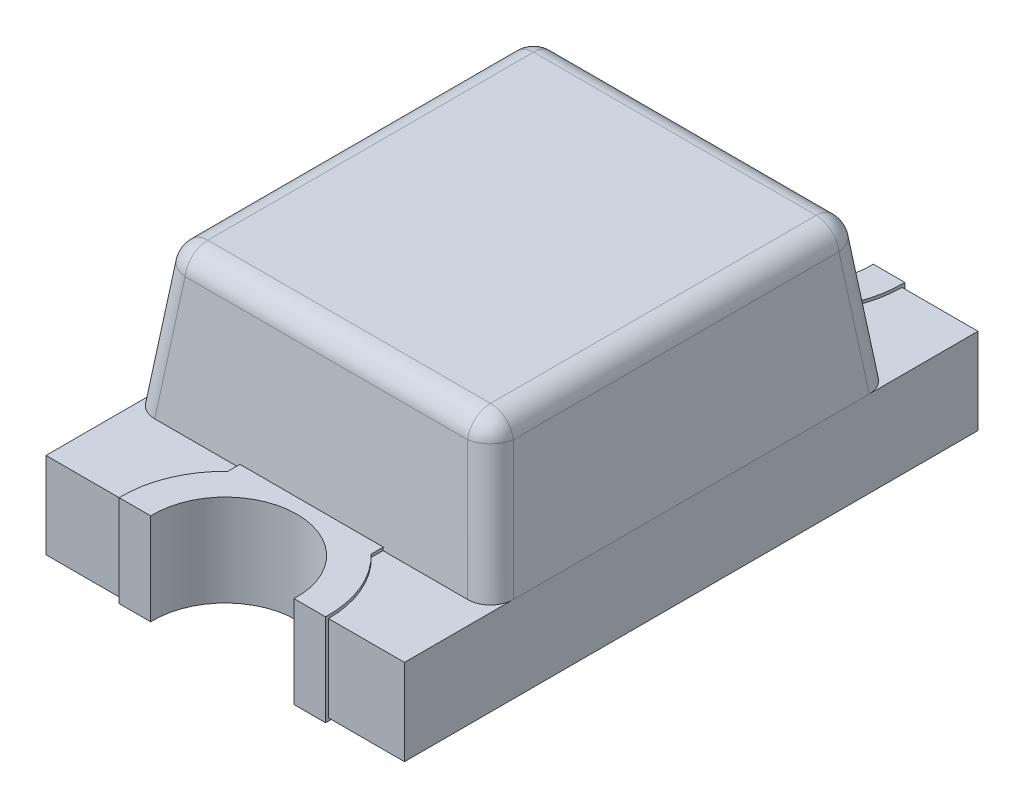
SolidWorks part; units mm, degrees
ref_plane "Front Plane" through (0, 0, 0) normal (0, 0, 1) x (1, 0, 0)
ref_plane "Top Plane" through (0, 0, 0) normal (0, 1, 0) x (1, 0, 0)
ref_plane "Right Plane" through (0, 0, 0) normal (1, 0, 0) x (0, 0, -1)
sketch "Sketch1" plane through (0, 0, 0) normal (0, 1, 0) x (1, 0, 0)
  line L0 (-0.625, 1) -> (0.625, -1) construction
  line L1 (-0.625, -1) -> (-0.25, -1)
  line L2 (-0.625, -1) -> (-0.625, 1)
  line L3 (-0.625, 1) -> (-0.25, 1)
  line L4 (0.625, -1) -> (0.625, 1)
  line L5 (-0.625, -1) -> (0.625, 1) construction
  line L6 (0.25, 1) -> (0.625, 1)
  line L7 (0.25, -1) -> (0.625, -1)
  arc A0 (-0.25, 1) -> (0.25, 1) centre (0, 1) ccw
  arc A1 (0.25, -1) -> (-0.25, -1) centre (0, -1) ccw
  dimension "D2" = 0.5
  dimension "D1" = 2
  dimension "D3" = 1.25
extrude "Base" add sketch "Sketch1" along normal mid plane 0.3
sketch "Sketch8" plane through (0, 0, 0) normal (0, 1, 0) x (1, 0, 0)
  line L0 (-0.25, -0.741) -> (-0.25, -0.6)
  line L1 (-0.25, -0.6) -> (0.25, -0.6)
  line L2 (0.25, -0.6) -> (0.25, -0.741)
  line L3 (-0.3599, 1.01) -> (-0.2498, 1.01)
  line L6 (-0.625, 1) -> (-0.625, -1)
  line L7 (-0.625, -1) -> (-0.25, -1)
  line L8 (0.25, -1) -> (0.625, -1)
  line L9 (0.625, -1) -> (0.625, 1)
  line L10 (0.625, 1) -> (0.25, 1)
  line L11 (-0.25, 1) -> (-0.625, 1)
  line L20 (0.2498, 1.01) -> (0.3599, 1.01)
  line L21 (0.625, 1) -> (0.25, 1) construction
  line L22 (-0.3599, -1.01) -> (-0.2498, -1.01)
  line L23 (0.2498, -1.01) -> (0.3599, -1.01)
  line L24 (0.25, -1) -> (0.625, -1) construction
  arc A0 (-0.3599, 1.01) -> (0.3599, 1.01) centre (0, 1) ccw
  arc A1 (0.3599, -1.01) -> (0.25, -0.741) centre (0, -1) ccw
  arc A2 (0.25, -1) -> (-0.25, -1) centre (0, -1) ccw
  arc A3 (-0.25, 1) -> (0.25, 1) centre (0, 1) ccw
  arc A4 (0.2498, -1.01) -> (-0.2498, -1.01) centre (0, -1) ccw
  arc A5 (-0.2498, 1.01) -> (0.2498, 1.01) centre (0, 1) ccw
  arc A6 (-0.25, -0.741) -> (-0.3599, -1.01) centre (0, -1) ccw
  arc A7 (-0.25, 1) -> (0.25, 1) centre (0, 1) ccw construction
  arc A8 (-0.36, 1) -> (0.36, 1) centre (0, 1) ccw construction
  dimension "D2" = 0.36
  dimension "D3" = 0.5
  dimension "D4" = 0.6
  dimension "D5" = 0.01
  dimension "D6" = 0.01
  dimension "D1" = 0
extrude "Lead top" add sketch "Sketch8" along normal mid plane 0.32
sketch "Sketch10" plane through (0, -0.16, 0) normal (0, -1, 0) x (1, 0, 0)
  line L0 (0, 0.6) -> (0, 0) construction
  line L5 (-0.25, 0.741) -> (-0.25, 0.6)
  line L6 (-0.25, 0.6) -> (0.25, 0.6)
  line L7 (0.3599, -1.01) -> (0.2498, -1.01) construction
  line L8 (-0.2498, -1.01) -> (-0.3599, -1.01) construction
  line L16 (-0.3599, 1.01) -> (-0.3599, 0.6)
  line L17 (-0.3599, 0.6) -> (0.3599, 0.6)
  line L18 (0.3599, 1.01) -> (0.3599, 0.6)
  line L19 (-0.3599, -0.6) -> (0.3599, -0.6)
  line L23 (0, 0) -> (0, -0.6) construction
  line L26 (0.36, 1) -> (0.625, 1) construction
  line L31 (0.3599, -1.01) -> (0.2498, -1.01)
  line L32 (-0.2498, -1.01) -> (-0.3599, -1.01)
  line L33 (-0.2498, 1.01) -> (-0.3599, 1.01)
  line L34 (-0.2498, 1.01) -> (-0.3599, 1.01)
  line L35 (0.25, 0.6) -> (0.25, 0.741)
  line L36 (0.3599, 1.01) -> (0.2498, 1.01)
  line L37 (0.3599, 1.01) -> (0.2498, 1.01)
  line L38 (0.3599, -1.01) -> (0.3599, -0.6)
  line L40 (-0.3599, -1.01) -> (-0.3599, -0.6)
  arc A3 (-0.2498, 1.01) -> (0.2498, 1.01) centre (0, 1) ccw
  arc A4 (-0.3599, 1.01) -> (-0.25, 0.741) centre (0, 1) ccw
  arc A5 (-0.2498, 1.01) -> (0.2498, 1.01) centre (0, 1) ccw
  arc A12 (0.2498, -1.01) -> (-0.2498, -1.01) centre (0, -1) ccw construction
  arc A16 (0.25, 0.741) -> (0.3599, 1.01) centre (0, 1) ccw
  arc A17 (0.2498, -1.01) -> (-0.2498, -1.01) centre (0, -1) ccw
  dimension "D3" = 0.4
  dimension "D1" = 0
extrude "Lead bottom" add sketch "Sketch10" against normal up to surface (0.01 mm away) up to face at (0, -0.15, 0.2516)
sketch "Sketch7" plane through (0, 0.15, 0) normal (0, 1, 0) x (1, 0, 0)
  line L0 (0.625, -1) -> (0.625, 1) construction
  line L1 (-0.625, -0.7) -> (0.625, -0.7)
  line L2 (-0.625, -0.7) -> (-0.625, 0.7)
  line L3 (-0.625, 0.7) -> (0.625, 0.7)
  line L4 (0.625, -0.7) -> (0.625, 0.7)
  line L5 (-0.625, -0.7) -> (0.625, 0.7) construction
  line L6 (-0.625, 0.7) -> (0.625, -0.7) construction
  point P0 (0, 0)
  dimension "D1" = 1.4
extrude "Lens" add sketch "Sketch7" along normal blind 0.5 draft 7
fillet "Fillet " radius 0.08 8 edges at (0, 0.65, 0.6386) (-0.5636, 0.65, 0) (0, 0.65, -0.6386) (0.5636, 0.65, 0) (0.5943, 0.4, -0.6693) (-0.5943, 0.4, -0.6693) (-0.5943, 0.4, 0.6693) (0.5943, 0.4, 0.6693)
